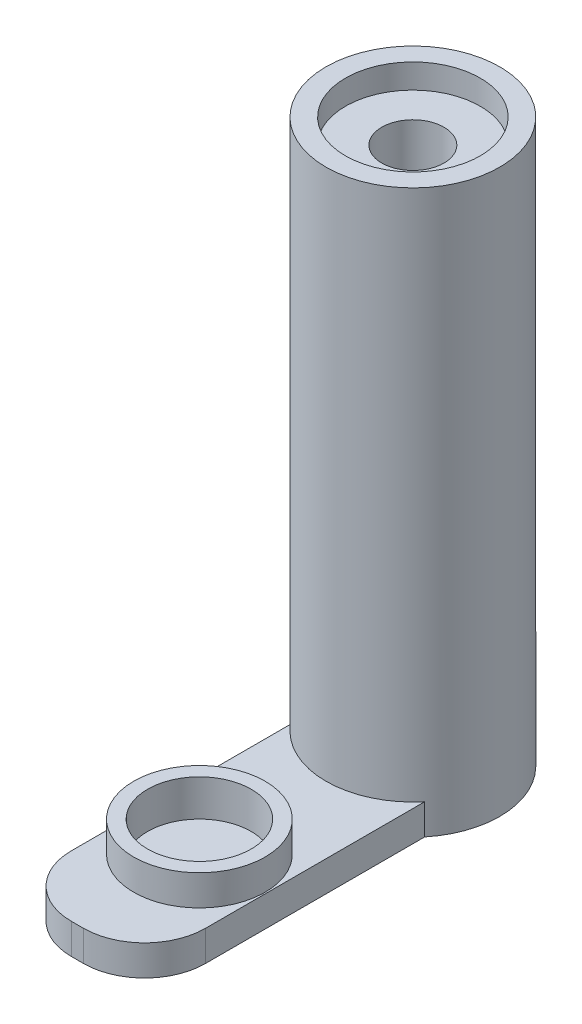
SolidWorks part; units mm, degrees
ref_plane "Front Plane" through (0, 0, 0) normal (0, 0, 1) x (1, 0, 0)
ref_plane "Top Plane" through (0, 0, 0) normal (0, 1, 0) x (1, 0, 0)
ref_plane "Right Plane" through (0, 0, 0) normal (1, 0, 0) x (0, 0, -1)
sketch "Sketch1" plane through (0, 0, 0) normal (0, 1, 0) x (1, 0, 0)
  circle A0 centre (0, 0) radius 14.25
  dimension "D1" = 28.5
extrude "Boss-Extrude1" add sketch "Sketch1" along normal blind 92.2
sketch "Sketch2" plane through (0, 92.2, 0) normal (0, 1, 0) x (1, 0, 0)
  circle A0 centre (0, 0) radius 5.1
  dimension "D1" = 10.2
extrude "Cut-Extrude1" cut sketch "Sketch2" against normal blind 92.2
sketch "Sketch3" plane through (0, 92.2, 0) normal (0, 1, 0) x (1, 0, 0)
  circle A0 centre (0, 0) radius 11.05
  dimension "D1" = 22.1
extrude "Cut-Extrude2" cut sketch "Sketch3" against normal blind 4
sketch "Sketch4" plane through (0, 0, 0) normal (0, -1, 0) x (1, 0, 0)
  line L1 (-11, 55) -> (11, 55)
  line L2 (-11, 55) -> (-11, 9.0588)
  line L4 (11, 55) -> (11, 9.0588)
  arc A1 (-11, 9.0588) -> (11, 9.0588) centre (0, 0) ccw
extrude "Boss-Extrude2" add sketch "Sketch4" against normal blind 5
sketch "Sketch5" plane through (0, 0, 0) normal (0, -1, 0) x (1, 0, 0)
  line L1 (0, 0) -> (0, 35) construction
  point P0 (0, 0)
  dimension "D1" = 35
sketch "Sketch6" plane through (0, 5, 0) normal (0, 1, 0) x (1, 0, 0)
  circle A0 centre (0, -35) radius 8.5
  dimension "D1" = 17
extrude "Cut-Extrude3" cut sketch "Sketch6" against normal blind 1
fillet "Fillet1" radius 10 2 edges at (-11, 2.5, 55) (11, 2.5, 55)
sketch "Sketch7" plane through (0, 5, 0) normal (0, 1, 0) x (1, 0, 0)
  circle A0 centre (0, -35) radius 8.5
  circle A1 centre (0, -35) radius 10.7735
extrude "Boss-Extrude3" add sketch "Sketch7" along normal blind 5
